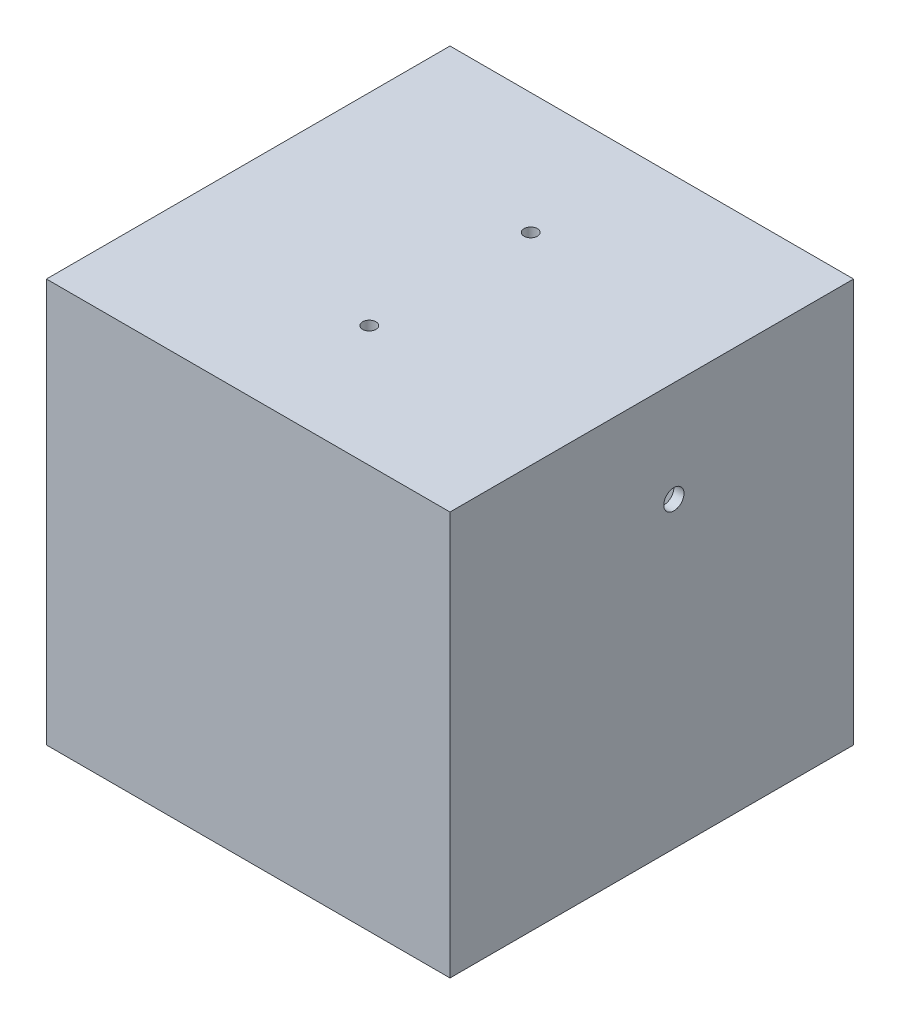
SolidWorks part; units mm, degrees
ref_plane "前视基准面" through (0, 0, 0) normal (0, 0, 1) x (1, 0, 0)
ref_plane "上视基准面" through (0, 0, 0) normal (0, 1, 0) x (1, 0, 0)
ref_plane "右视基准面" through (0, 0, 0) normal (1, 0, 0) x (0, 0, -1)
sketch "草图1" plane through (0, 0, 0) normal (0, 1, 0) x (1, 0, 0)
  line L1 (0, 0) -> (200, 0)
  line L2 (0, 0) -> (0, 200)
  line L3 (0, 200) -> (200, 200)
  line L4 (200, 0) -> (200, 200)
  dimension "D1" = 200
  dimension "D2" = 200
extrude "凸台-拉伸1" add sketch "草图1" along normal blind 5
sketch "草图3" plane through (0, 0, 0) normal (0, -1, 0) x (1, 0, 0)
  line L0 (0, -100) -> (200, -100) construction
  line L1 (0, -200) -> (0, 0) construction
  line L2 (200, 0) -> (200, -200) construction
  line L3 (0, 0) -> (200, 0) construction
  line L4 (0, -200) -> (200, -200)
  line L5 (0, -200) -> (0, 0)
  line L6 (0, 0) -> (200, 0)
  line L7 (200, -200) -> (200, 0)
  line L8 (0, -200) -> (200, 0) construction
  line L9 (0, 0) -> (200, -200) construction
  line L11 (5, -5) -> (195, -5)
  line L12 (5, -5) -> (5, -195)
  line L13 (5, -195) -> (195, -195)
  line L14 (195, -5) -> (195, -195)
  line L15 (5, -5) -> (195, -195) construction
  line L16 (5, -195) -> (195, -5) construction
  point P6 (100, -100)
  point P13 (100, -100)
  dimension "D1" = 190
extrude "凸台-拉伸2" add sketch "草图3" along normal blind 190
sketch "草图4" plane through (0, -190, 0) normal (0, -1, 0) x (1, 0, 0)
  line L0 (100, 0) -> (100, -200) construction
  line L1 (0, 0) -> (200, 0)
  line L2 (0, 0) -> (0, -200)
  line L3 (0, -200) -> (200, -200)
  line L4 (200, 0) -> (200, -200)
  circle A0 centre (100, -100) radius 70
  dimension "D1" = 140
extrude "凸台-拉伸3" add sketch "草图4" along normal blind 5
sketch "草图5" plane through (0, 5, 0) normal (0, 1, 0) x (1, 0, 0)
  line L0 (0, 100) -> (200, 100) construction
  line L1 (0, 200) -> (0, 0) construction
  line L2 (200, 0) -> (200, 200) construction
  line L3 (100, 100) -> (100, 200) construction
  line L4 (200, 200) -> (0, 200) construction
  circle A0 centre (100, 140) radius 3.3
  circle A1 centre (100, 60) radius 3.3
  dimension "D1" = 6.6
  dimension "D2" = 40
extrude "切除-拉伸1" cut sketch "草图5" against normal blind 5
sketch "草图7" plane through (200, 0, 0) normal (1, 0, 0) x (0, 0, -1)
  line L0 (200, 5) -> (200, -195) construction
  line L4 (0, 5) -> (200, 5) construction
  circle A0 centre (110.95, -45) radius 5
  point P4 (130.3362, 5)
  point P5 (0, 0)
  dimension "D2" = 10
  dimension "D1" = 89.05
  dimension "D3" = 50
extrude "切除-拉伸2" cut sketch "草图7" against normal through all
